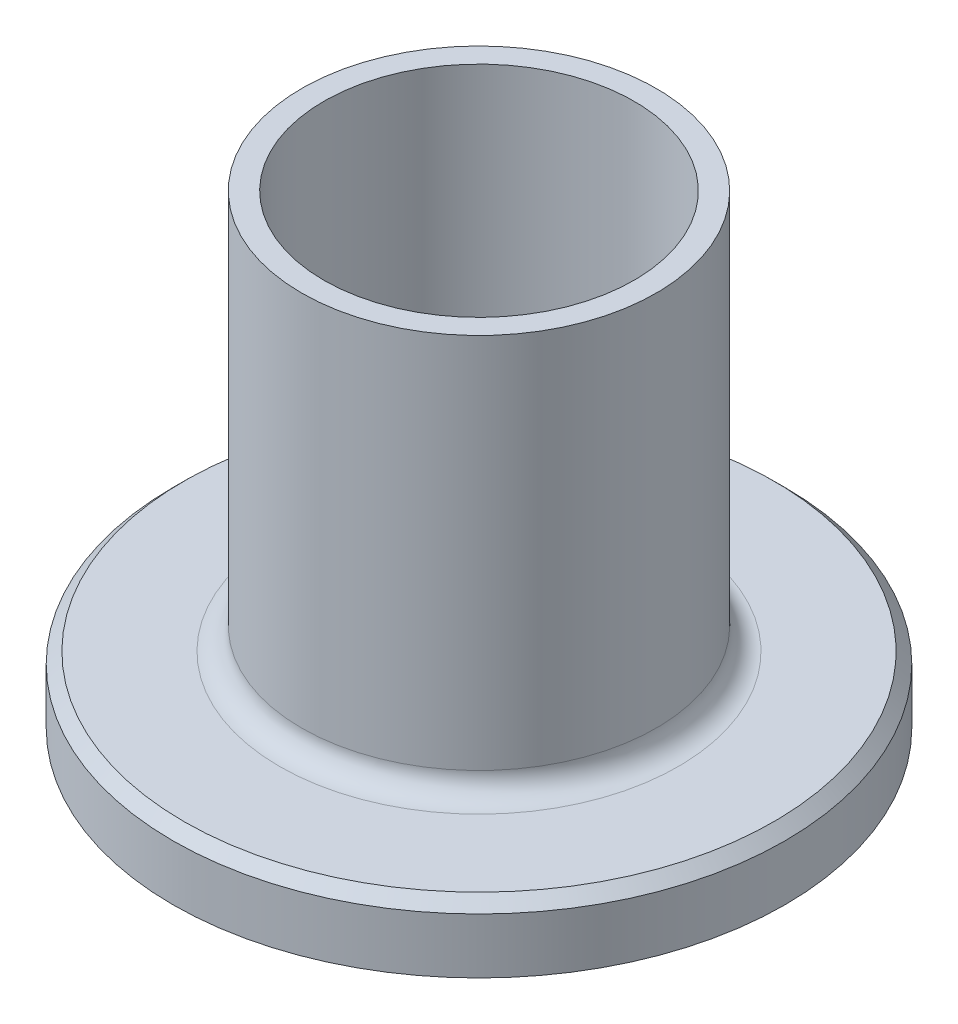
SolidWorks part; units mm, degrees
ref_plane "Front Plane" through (0, 0, 0) normal (0, 0, 1) x (1, 0, 0)
ref_plane "Top Plane" through (0, 0, 0) normal (0, 1, 0) x (1, 0, 0)
ref_plane "Right Plane" through (0, 0, 0) normal (1, 0, 0) x (0, 0, -1)
sketch "Sketch1" plane through (0, 0, 0) normal (0, 1, 0) x (1, 0, 0)
  circle A0 centre (0, 0) radius 27.62
  dimension "D1" = 55.24
extrude "Boss-Extrude1" add sketch "Sketch1" along normal blind 6
sketch "Sketch2" plane through (0, 6, 0) normal (0, 1, 0) x (1, 0, 0)
  circle A0 centre (0, 0) radius 16
  circle A1 centre (0, 0) radius 14
  dimension "D1" = 32
  dimension "D2" = 28
extrude "Boss-Extrude2" add sketch "Sketch2" along normal blind 36
sketch "Sketch3" plane through (0, 6, 0) normal (0, 1, 0) x (1, 0, 0)
  circle A0 centre (0, 0) radius 14 construction
  circle A1 centre (0, 0) radius 14
extrude "Cut-Extrude1" cut sketch "Sketch3" against normal blind 36
chamfer "Chamfer1" distance 5 angle 55 1 edges at (0, 0, 14)
chamfer "Chamfer2" distance 1 angle 45 1 edges at (0, 6, 27.62)
sketch "Sketch4" plane through (0, 0, 0) normal (0, -1, 0) x (1, 0, 0)
  circle A3 centre (0, 0) radius 25
  circle A5 centre (0, 0) radius 27
  dimension "D1" = 50
  dimension "D2" = 2
extrude "Cut-Extrude2" cut sketch "Sketch4" against normal blind 1.6
fillet "Fillet1" radius 2 1 edges at (0, 6, 16)
fillet "Fillet2" radius 4 1 edges at (0, 5, 14)
